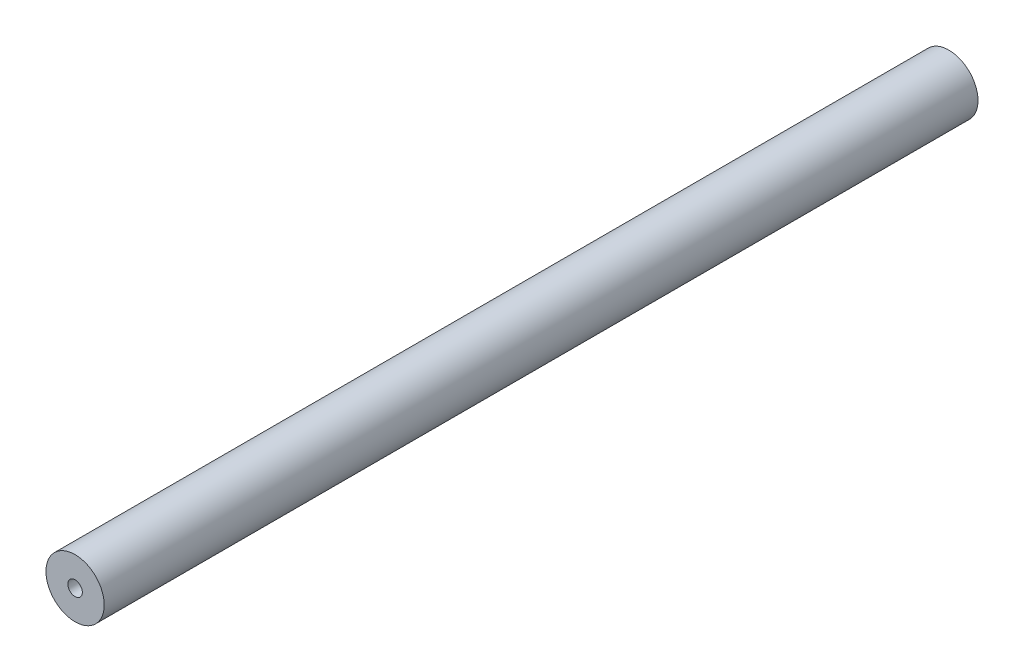
SolidWorks part; units mm, degrees
ref_plane "Front Plane" through (0, 0, 0) normal (0, 0, 1) x (1, 0, 0)
ref_plane "Top Plane" through (0, 0, 0) normal (0, 1, 0) x (1, 0, 0)
ref_plane "Right Plane" through (0, 0, 0) normal (1, 0, 0) x (0, 0, -1)
sketch "Sketch1" plane through (0, 0, 0) normal (0, 0, 1) x (1, 0, 0)
  circle A0 centre (0, 0) radius 40
  dimension "D1" = 80
extrude "Boss-Extrude1" add sketch "Sketch1" along normal blind 1200
sketch "Sketch3" plane through (0, 0, 1200) normal (0, 0, 1) x (1, 0, 0)
  circle A0 centre (0, 0) radius 10
  dimension "D1" = 20
extrude "Cut-Extrude1" cut sketch "Sketch3" against normal blind 1100
